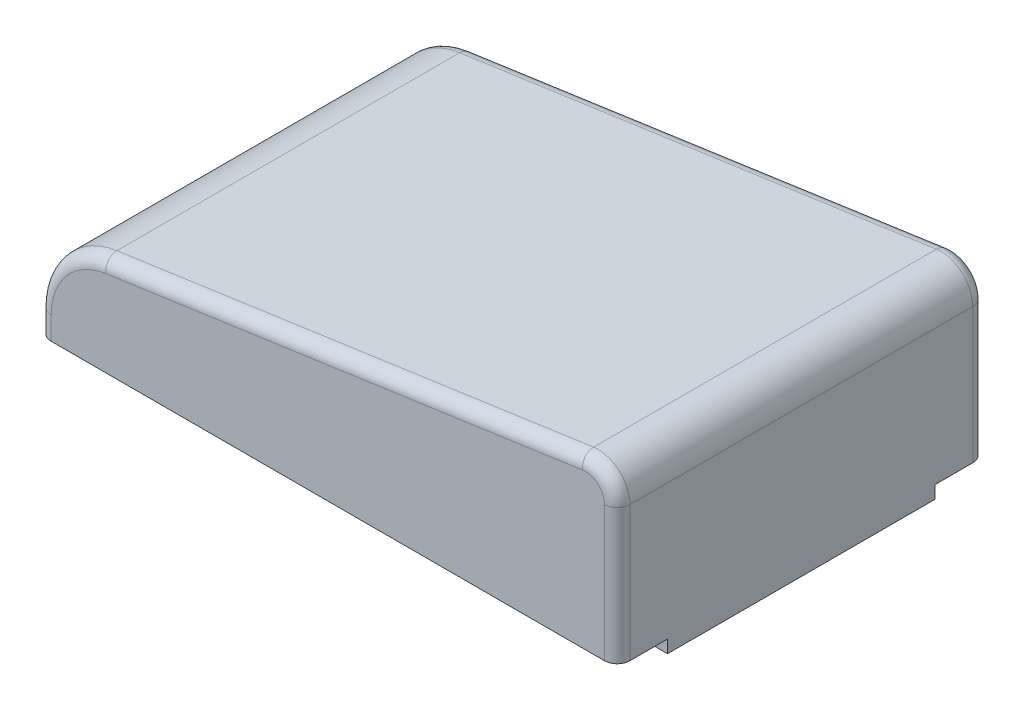
SolidWorks part; units mm, degrees
ref_plane "Front Plane" through (0, 0, 0) normal (0, 0, 1) x (1, 0, 0)
ref_plane "Top Plane" through (0, 0, 0) normal (0, 1, 0) x (1, 0, 0)
ref_plane "Right Plane" through (0, 0, 0) normal (1, 0, 0) x (0, 0, -1)
sketch "Sketch1" plane through (0, 0, 0) normal (0, 1, 0) x (1, 0, 0)
  line L0 (-3.9926, 28.9) -> (-3.9926, 0)
  line L1 (-1.9926, 26.9) -> (84.8274, 26.9)
  line L2 (-1.9926, 26.9) -> (-1.9926, 0)
  line L4 (84.8274, 26.9) -> (84.8274, 0)
  line L6 (86.8274, 28.9) -> (86.8274, 0)
  line L7 (-3.9926, 28.9) -> (86.8274, 28.9)
  line L8 (96.3693, 0) -> (-100.3545, 0) construction
  line L9 (-3.9926, 0) -> (-1.9926, 0)
  line L10 (84.8274, 0) -> (86.8274, 0)
  line L11 (-1.9926, -26.9) -> (-1.9926, -21) construction
  line L12 (84.8274, 26.9) -> (-1.9926, 26.9) construction
  dimension "D1" = 2
  dimension "D2" = 2
  dimension "D4" = 2
  dimension "D5" = 86.82
extrude "Boss-Extrude1" add sketch "Sketch1" along normal blind 25
sketch "Sketch2" plane through (0, 0, 0) normal (0, 0, 1) x (1, 0, 0)
  line L1 (-3.9926, 0) -> (86.8274, 0)
  line L2 (-3.9926, 0) -> (-3.9926, 12)
  line L3 (-3.9926, 12) -> (86.8274, 25)
  line L4 (86.8274, 0) -> (86.8274, 25)
  dimension "D1" = 12
extrude "Cut-Extrude1" cut sketch "Sketch2" against normal up to next flip side to cut
sketch "Sketch4" plane through (-1.7634, 12.3191, 0) normal (-0.1417, 0.9899, 0) x (0.9899, 0.1417, 0)
  line L1 (-2.2519, 0) -> (89.4937, 0)
  line L4 (89.4937, 28.9) -> (-2.2519, 28.9)
  line L5 (-2.2519, 28.9) -> (-2.2519, 0)
  line L6 (-2.2519, 0) -> (-0.2316, 0)
  line L7 (89.4937, 0) -> (89.4937, 28.9)
  line L8 (89.4937, 28.9) -> (-2.2519, 28.9)
  line L9 (-2.2519, 28.9) -> (-2.2519, 0)
  line L11 (89.4937, 0) -> (89.4937, 28.9)
  line L17 (-0.2316, 0) -> (-0.2316, 26.9)
  line L19 (-0.2316, 26.9) -> (87.4734, 26.9)
  line L21 (87.4734, 26.9) -> (87.4734, 0)
  line L23 (87.4734, 0) -> (89.4937, 0)
  dimension "D1" = 0
extrude "Boss-Extrude2" add sketch "Sketch4" along direction (0, -1, 0) on the side of the normal blind 2
fillet "Fillet4" radius 10 1 edges at (-1.9926, 12.2863, -13.45)
fillet "Fillet5" radius 12 1 edges at (-3.9926, 14, -14.45)
fillet "Fillet3" radius 3 1 edges at (84.8274, 24.7137, -13.45)
fillet "Fillet2" radius 5 1 edges at (86.8274, 27, -14.45)
fillet "Fillet1" radius 2 5 edges at (86.8274, 10.6167, -28.9) (-3.9926, 1.7977, -28.9) (85.1029, 25.0111, -28.9) (43.713, 20.8286, -28.9) (-1.0591, 11.4565, -28.9)
sketch "Sketch5" plane through (0, 0, 0) normal (0, 1, 0) x (1, 0, 0)
  line L0 (-5.6941, 0) -> (90.9466, 0) construction
  line L1 (-3.9926, 0) -> (-1.9926, 0)
  line L3 (-3.9926, 21) -> (-3.9926, 0)
  line L5 (-1.9926, 21) -> (-1.9926, 0)
  line L6 (-3.9926, 21) -> (-1.9926, 21)
  line L7 (84.8274, 21) -> (86.8274, 21)
  line L8 (84.8274, 21) -> (84.8274, 0)
  line L9 (86.8274, 21) -> (86.8274, 0)
  line L11 (84.8274, 0) -> (86.8274, 0)
  dimension "D1" = 2
  dimension "D2" = 2
extrude "Boss-Extrude3" add sketch "Sketch5" against normal blind 2
sketch "Sketch7" plane through (0, 0, -26.9) normal (0, 0, 1) x (1, 0, 0)
  line L4 (84.8274, 0) -> (84.8274, 21.2537)
  line L5 (81.4023, 24.2235) -> (6.5905, 13.5149)
  line L6 (-1.9926, 3.6158) -> (-1.9926, 0)
  line L7 (-1.9926, 0) -> (84.8274, 0)
  line L8 (84.8274, 0) -> (84.8274, 21.2537)
  line L10 (-1.9926, 3.6158) -> (-1.9926, 0)
  line L11 (-1.9926, 0) -> (84.8274, 0)
  line L13 (81.4023, 24.2235) -> (6.5905, 13.5149)
  arc A1 (6.5905, 13.5149) -> (-1.9926, 3.6158) centre (8.0074, 3.6158) ccw
  arc A3 (6.5905, 13.5149) -> (-1.9926, 3.6158) centre (8.0074, 3.6158) ccw
  arc A8 (84.8274, 21.2537) -> (81.4023, 24.2235) centre (81.8274, 21.2537) ccw
  arc A9 (84.8274, 21.2537) -> (81.4023, 24.2235) centre (81.8274, 21.2537) ccw
  dimension "D1" = 0
extrude "Boss-Extrude5" [suppressed] add sketch "Sketch7" along normal blind 1.5
sketch "Sketch10" plane through (0, 0, 0) normal (0, 1, 0) x (1, 0, 0)
  line L12 (-1.9926, 26.7) -> (8.0074, 26.7)
  line L13 (8.0074, 26.7) -> (8.0074, 25.4)
  line L14 (8.0074, 25.4) -> (-1.9926, 25.4)
  line L15 (-1.9926, 25.4) -> (-1.9926, 26.7)
  dimension "D1" = 1.3
  dimension "D3" = 10
extrude "Boss-Extrude6" add sketch "Sketch10" against normal blind 2 and the other way up to next
mirror "Mirror6" about plane through (0, 0, 0) normal (0, 0, 1) of bodies 107
sketch "Sketch11" plane through (0, 0, 0) normal (0, 1, 0) x (1, 0, 0)
  line L0 (-54.4003, 0) -> (44.676, 0) construction
  line L2 (-3.9926, -26.9) -> (-3.9926, 26.9) construction
  circle A0 centre (7.0074, 0) radius 3.5
  dimension "D1" = 7
  dimension "D2" = 11
extrude "Boss-Extrude7" add sketch "Sketch11" along normal up to next and the other way blind 24.5
chamfer "Chamfer1" distance 0.4 angle 45 1 edges at (7.0074, -24.5, 3.5)
sketch "Sketch12" plane through (0, -24.5, 0) normal (0, -1, 0) x (1, 0, 0)
  circle A0 centre (7.0074, 0) radius 1.8
extrude "Cut-Extrude2" cut sketch "Sketch12" against normal blind 6
